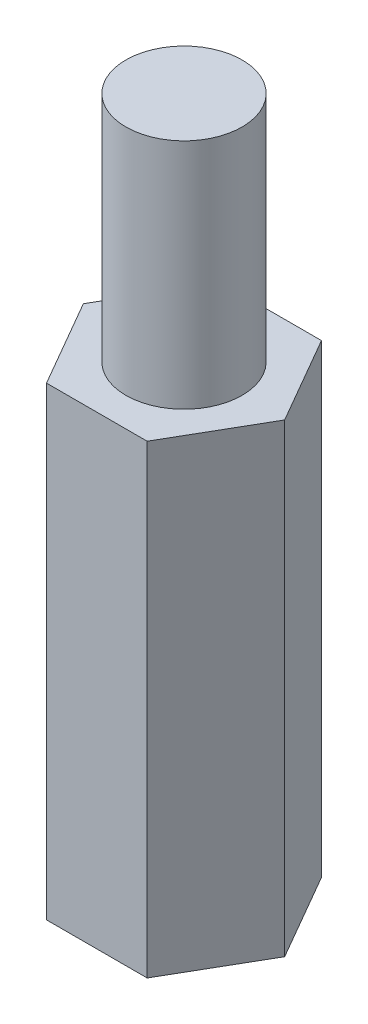
SolidWorks part; units mm, degrees
material "Commercial Bronze, UNS C22000 (90-10 Bronze)"
ref_plane "Front Plane" through (0, 0, 0) normal (0, 0, 1) x (1, 0, 0)
ref_plane "Top Plane" through (0, 0, 0) normal (0, 1, 0) x (1, 0, 0)
ref_plane "Right Plane" through (0, 0, 0) normal (1, 0, 0) x (0, 0, -1)
sketch "Sketch1" plane through (0, 0, 0) normal (0, 1, 0) x (1, 0, 0)
  line L1 (2.5981, 0) -> (1.299, 2.25)
  line L2 (1.299, 2.25) -> (-1.299, 2.25)
  line L3 (-1.299, 2.25) -> (-2.5981, 0)
  line L4 (-2.5981, 0) -> (-1.299, -2.25)
  line L5 (-1.299, -2.25) -> (1.299, -2.25)
  line L6 (1.299, -2.25) -> (2.5981, 0)
  circle A0 centre (0, 0) radius 2.25 construction
  circle A1 centre (0, 0) radius 1.5
  dimension "D1" = 4.5
  dimension "D2" = 3
extrude "Boss-Extrude1" add sketch "Sketch1" along normal blind 12
sketch "Sketch2" plane through (0, 12, 0) normal (0, 1, 0) x (1, 0, 0)
  line L1 (2.5981, 0) -> (1.299, 2.25)
  line L2 (1.299, 2.25) -> (-1.299, 2.25)
  line L3 (-1.299, 2.25) -> (-2.5981, 0)
  line L4 (-2.5981, 0) -> (-1.299, -2.25)
  line L5 (-1.299, -2.25) -> (1.299, -2.25)
  line L6 (1.299, -2.25) -> (2.5981, 0)
  circle A0 centre (0, 0) radius 2.25 construction
extrude "Boss-Extrude2" add sketch "Sketch2" against normal blind 3
sketch "Sketch3" plane through (0, 12, 0) normal (0, 1, 0) x (1, 0, 0)
  circle A0 centre (0, 0) radius 1.5
  dimension "D1" = 3
extrude "Boss-Extrude3" add sketch "Sketch3" along normal blind 6
